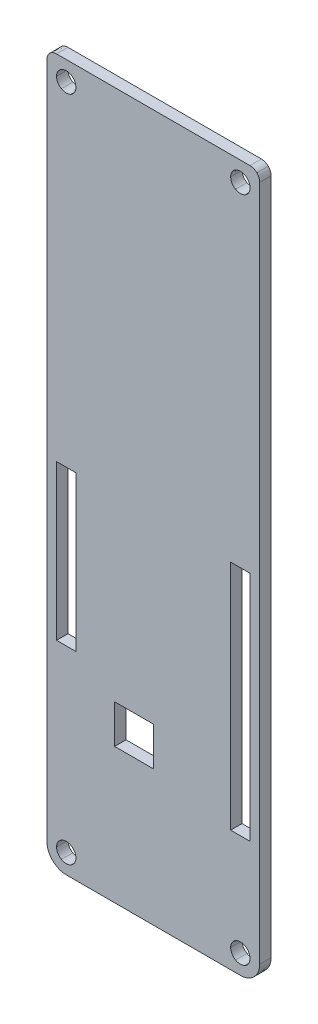
SolidWorks part; units mm, degrees
material "Verre"
ref_plane "Plan de face" through (0, 0, 0) normal (0, 0, 1) x (1, 0, 0)
ref_plane "Plan de dessus" through (0, 0, 0) normal (0, 1, 0) x (1, 0, 0)
ref_plane "Plan de droite" through (0, 0, 0) normal (1, 0, 0) x (0, 0, -1)
sketch "Model" plane through (0, 0, 0) normal (0, 0, 1) x (1, 0, 0)
  line L1651 (106.68, -110.3789) -> (106.68, -79.8989)
  line L1652 (109.22, -110.3789) -> (106.68, -110.3789)
  line L1653 (109.22, -79.8989) -> (109.22, -110.3789)
  line L1654 (106.68, -79.8989) -> (109.22, -79.8989)
  line L1655 (86.36, -100.2189) -> (86.36, -79.8989)
  line L1656 (83.82, -100.2189) -> (86.36, -100.2189)
  line L1657 (83.82, -79.8989) -> (83.82, -100.2189)
  line L1658 (86.36, -79.8989) -> (83.82, -79.8989)
  line L1659 (91.44, -108.4739) -> (91.44, -103.3939)
  line L1660 (96.52, -108.4739) -> (91.44, -108.4739)
  line L1661 (96.52, -103.3939) -> (96.52, -108.4739)
  line L1662 (91.44, -103.3939) -> (96.52, -103.3939)
  line L1773 (110.49, -34.8139) -> (110.49, -38.6239)
  line L1774 (83.82, -33.5439) -> (109.22, -33.5439)
  line L1775 (82.55, -38.6239) -> (82.55, -34.8139)
  line L1776 (82.55, -39.8939) -> (82.55, -123.7139)
  line L1777 (110.49, -39.8939) -> (110.49, -123.7139)
  line L1778 (82.55, -39.8939) -> (82.55, -38.6239)
  line L1779 (110.49, -39.8939) -> (110.49, -38.6239)
  line L1780 (85.09, -126.2539) -> (107.95, -126.2539)
  spline S0 degree 3 poles (109.22, -36.0839) (109.22, -36.5377) (108.9779, -36.9569) (108.585, -37.1838) knots 0 0 0 0 1 1 1 1
  spline S1 degree 3 poles (108.585, -37.1838) (108.1921, -37.4106) (107.7079, -37.4106) (107.315, -37.1838) knots 0 0 0 0 1 1 1 1
  spline S2 degree 3 poles (107.315, -37.1838) (106.9221, -36.9569) (106.68, -36.5377) (106.68, -36.0839) knots 0 0 0 0 1 1 1 1
  spline S3 degree 3 poles (106.68, -36.0839) (106.68, -35.6302) (106.9221, -35.2109) (107.315, -34.9841) knots 0 0 0 0 1 1 1 1
  spline S4 degree 3 poles (107.315, -34.9841) (107.7079, -34.7572) (108.1921, -34.7572) (108.585, -34.9841) knots 0 0 0 0 1 1 1 1
  spline S5 degree 3 poles (108.585, -34.9841) (108.9779, -35.2109) (109.22, -35.6302) (109.22, -36.0839) knots 0 0 0 0 1 1 1 1
  spline S6 degree 3 poles (86.36, -36.0839) (86.36, -36.5377) (86.1179, -36.9569) (85.725, -37.1838) knots 0 0 0 0 1 1 1 1
  spline S7 degree 3 poles (85.725, -37.1838) (85.3321, -37.4106) (84.8479, -37.4106) (84.455, -37.1838) knots 0 0 0 0 1 1 1 1
  spline S8 degree 3 poles (84.455, -37.1838) (84.0621, -36.9569) (83.82, -36.5377) (83.82, -36.0839) knots 0 0 0 0 1 1 1 1
  spline S9 degree 3 poles (83.82, -36.0839) (83.82, -35.6302) (84.0621, -35.2109) (84.455, -34.9841) knots 0 0 0 0 1 1 1 1
  spline S10 degree 3 poles (84.455, -34.9841) (84.8479, -34.7572) (85.3321, -34.7572) (85.725, -34.9841) knots 0 0 0 0 1 1 1 1
  spline S11 degree 3 poles (85.725, -34.9841) (86.1179, -35.2109) (86.36, -35.6302) (86.36, -36.0839) knots 0 0 0 0 1 1 1 1
  spline S12 degree 3 poles (110.49, -34.8139) (110.49, -34.4771) (110.3562, -34.1541) (110.118, -33.9159) knots 0 0 0 0 1 1 1 1
  spline S13 degree 3 poles (110.118, -33.9159) (109.8799, -33.6777) (109.5568, -33.5439) (109.22, -33.5439) knots 0 0 0 0 1 1 1 1
  spline S14 degree 3 poles (83.82, -33.5439) (83.4832, -33.5439) (83.1601, -33.6777) (82.922, -33.9159) knots 0 0 0 0 1 1 1 1
  spline S15 degree 3 poles (82.922, -33.9159) (82.6838, -34.1541) (82.55, -34.4771) (82.55, -34.8139) knots 0 0 0 0 1 1 1 1
  spline S16 degree 3 poles (82.55, -123.7139) (82.55, -124.3876) (82.8176, -125.0336) (83.2939, -125.51) knots 0 0 0 0 1 1 1 1
  spline S17 degree 3 poles (83.2939, -125.51) (83.7703, -125.9863) (84.4163, -126.2539) (85.09, -126.2539) knots 0 0 0 0 1 1 1 1
  spline S18 degree 3 poles (107.95, -126.2539) (108.6236, -126.2539) (109.2697, -125.9863) (109.7461, -125.51) knots 0 0 0 0 1 1 1 1
  spline S19 degree 3 poles (109.7461, -125.51) (110.2224, -125.0336) (110.49, -124.3876) (110.49, -123.7139) knots 0 0 0 0 1 1 1 1
  spline S20 degree 3 poles (86.36, -123.7139) (86.36, -124.1677) (86.1179, -124.5869) (85.725, -124.8138) knots 0 0 0 0 1 1 1 1
  spline S21 degree 3 poles (85.725, -124.8138) (85.3321, -125.0406) (84.8479, -125.0406) (84.455, -124.8138) knots 0 0 0 0 1 1 1 1
  spline S22 degree 3 poles (84.455, -124.8138) (84.0621, -124.5869) (83.82, -124.1677) (83.82, -123.7139) knots 0 0 0 0 1 1 1 1
  spline S23 degree 3 poles (83.82, -123.7139) (83.82, -123.2602) (84.0621, -122.8409) (84.455, -122.6141) knots 0 0 0 0 1 1 1 1
  spline S24 degree 3 poles (84.455, -122.6141) (84.8479, -122.3872) (85.3321, -122.3872) (85.725, -122.6141) knots 0 0 0 0 1 1 1 1
  spline S25 degree 3 poles (85.725, -122.6141) (86.1179, -122.8409) (86.36, -123.2602) (86.36, -123.7139) knots 0 0 0 0 1 1 1 1
  spline S26 degree 3 poles (109.22, -123.7139) (109.22, -124.1677) (108.9779, -124.5869) (108.585, -124.8138) knots 0 0 0 0 1 1 1 1
  spline S27 degree 3 poles (108.585, -124.8138) (108.1921, -125.0406) (107.7079, -125.0406) (107.315, -124.8138) knots 0 0 0 0 1 1 1 1
  spline S28 degree 3 poles (107.315, -124.8138) (106.9221, -124.5869) (106.68, -124.1677) (106.68, -123.7139) knots 0 0 0 0 1 1 1 1
  spline S29 degree 3 poles (106.68, -123.7139) (106.68, -123.2602) (106.9221, -122.8409) (107.315, -122.6141) knots 0 0 0 0 1 1 1 1
  spline S30 degree 3 poles (107.315, -122.6141) (107.7079, -122.3872) (108.1921, -122.3872) (108.585, -122.6141) knots 0 0 0 0 1 1 1 1
  spline S31 degree 3 poles (108.585, -122.6141) (108.9779, -122.8409) (109.22, -123.2602) (109.22, -123.7139) knots 0 0 0 0 1 1 1 1
extrude "Boss.-Extru.1" add sketch "Model" along normal blind 1.5
